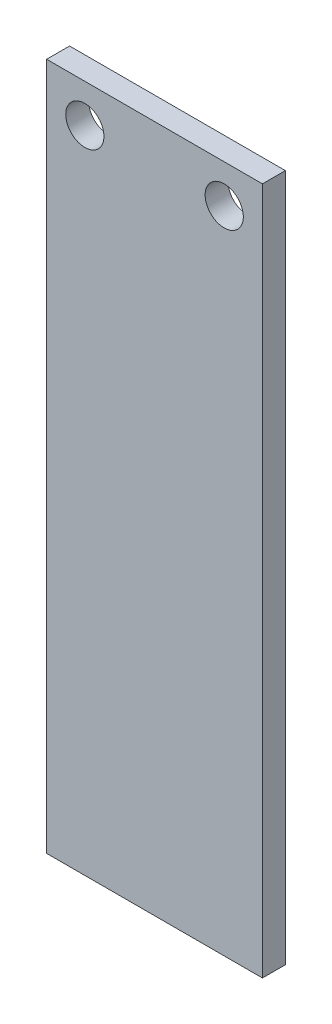
SolidWorks part; units mm, degrees
ref_plane "Front Plane" through (0, 0, 0) normal (0, 0, 1) x (1, 0, 0)
ref_plane "Top Plane" through (0, 0, 0) normal (0, 1, 0) x (1, 0, 0)
ref_plane "Right Plane" through (0, 0, 0) normal (1, 0, 0) x (0, 0, -1)
sketch "Sketch1" plane through (0, 0, 0) normal (0, 0, 1) x (1, 0, 0)
  line L1 (-14.12, 40) -> (14.12, 40)
  line L2 (-14.12, 40) -> (-14.12, -40)
  line L3 (-14.12, -40) -> (14.12, -40)
  line L4 (14.12, 40) -> (14.12, -40)
  line L5 (-14.12, 40) -> (14.12, -40) construction
  line L6 (-14.12, -40) -> (14.12, 40) construction
  point P0 (0, 0)
  dimension "D1" = 28.24
  dimension "D2" = 80
extrude "Boss-Extrude1" add sketch "Sketch1" along normal blind 3
sketch "Sketch3" plane through (0, 0, 0) normal (0, 0, -1) x (-1, 0, 0)
  line L1 (14.12, 40) -> (-14.12, 40)
  line L2 (14.12, 40) -> (14.12, 50)
  line L3 (14.12, 50) -> (-14.12, 50)
  line L4 (-14.12, 40) -> (-14.12, 50)
  point P5 (0, 0)
  dimension "D1" = 10
extrude "Boss-Extrude3" add sketch "Sketch3" against normal blind 3
sketch "Sketch4" plane through (0, 0, 0) normal (0, 0, -1) x (-1, 0, 0)
  line L0 (14.12, 50) -> (14.12, -40) construction
  line L1 (14.12, 50) -> (-14.12, 50) construction
  circle A0 centre (9.12, 45) radius 2.5
  dimension "D1" = 5
  dimension "D2" = 5
  dimension "D3" = 5
extrude "Cut-Extrude1" cut sketch "Sketch4" against normal up to next
mirror "Mirror1" about plane through (0, 0, 0) normal (1, 0, 0) of "Cut-Extrude1"
